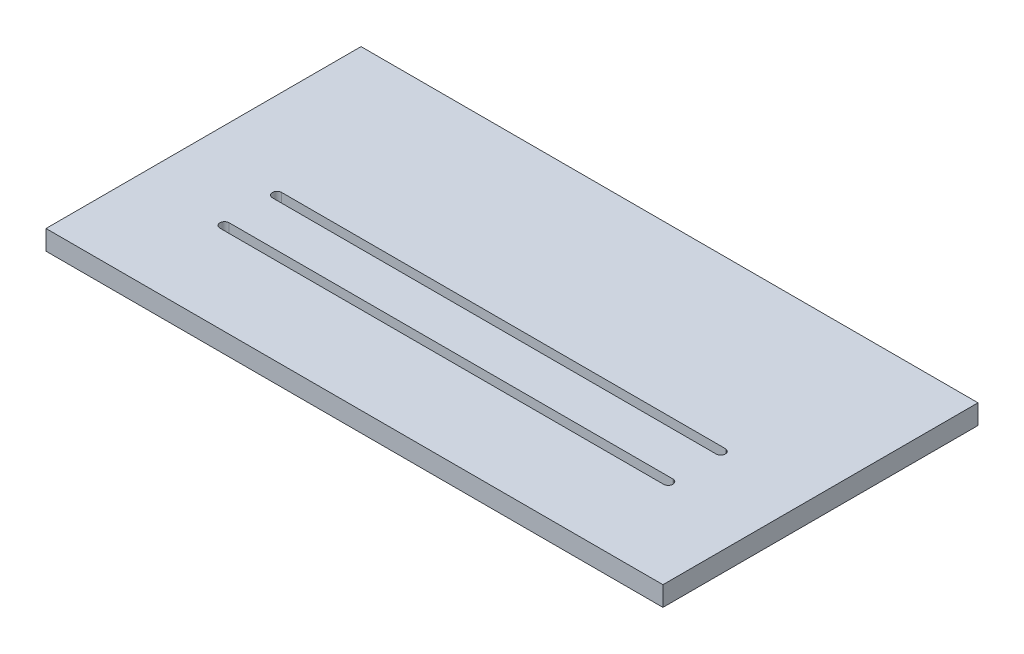
SolidWorks part; units mm, degrees
material "Acrylic (Medium-high impact)"
ref_plane "Front Plane" through (0, 0, 0) normal (0, 0, 1) x (1, 0, 0)
ref_plane "Top Plane" through (0, 0, 0) normal (0, 1, 0) x (1, 0, 0)
ref_plane "Right Plane" through (0, 0, 0) normal (1, 0, 0) x (0, 0, -1)
sketch "Sketch1" plane through (0, 0, 0) normal (0, 1, 0) x (1, 0, 0)
  line L1 (-149.225, -76.2) -> (149.225, -76.2)
  line L2 (-149.225, -76.2) -> (-149.225, 76.2)
  line L3 (-149.225, 76.2) -> (149.225, 76.2)
  line L4 (149.225, -76.2) -> (149.225, 76.2)
  line L5 (-149.225, -76.2) -> (149.225, 76.2) construction
  line L6 (-149.225, 76.2) -> (149.225, -76.2) construction
  line L7 (73.025, -76.2) -> (-130.175, -76.2)
  line L11 (-384.175, -76.2) -> (-231.775, -76.2)
  point P0 (0, 0)
  dimension "D1" = 298.45
  dimension "D2" = 152.4
extrude "Boss-Extrude1" add sketch "Sketch1" along normal mid plane 9.525 contours L1 L4 L3 L2
sketch "Sketch2" [suppressed] plane through (0, 0, 0) normal (0, 1, 0) x (1, 0, 0)
  line L0 (-250.825, -28.575) -> (250.825, -28.575) construction
  line L1 (161.925, -28.575) -> (60.325, -28.575)
  line L2 (161.925, -28.575) -> (161.925, -92.075)
  line L3 (161.925, -92.075) -> (60.325, -92.075)
  line L4 (60.325, -28.575) -> (60.325, -92.075)
  line L5 (0, -5.2388) -> (0, 5.2388) construction
  line L6 (-79.375, -28.575) -> (-168.275, -28.575)
  line L7 (-79.375, -28.575) -> (-79.375, -92.075)
  line L8 (-79.375, -92.075) -> (-168.275, -92.075)
  line L9 (-168.275, -28.575) -> (-168.275, -92.075)
  line L10 (250.825, -28.575) -> (250.825, 28.575) construction
  line L11 (-250.825, -28.575) -> (-250.825, 28.575) construction
  line L12 (-250.825, 28.575) -> (250.825, 28.575) construction
  line L13 (250.825, -28.575) -> (250.825, 28.575) construction
  line L14 (161.925, -28.575) -> (250.825, -28.575)
  line L15 (161.925, -28.575) -> (161.925, -71.755)
  line L16 (161.925, -71.755) -> (250.825, -71.755)
  line L17 (250.825, -28.575) -> (250.825, -71.755)
  line L18 (-250.825, -28.575) -> (-250.825, 28.575) construction
  line L19 (-79.375, -28.575) -> (60.325, -28.575)
  line L20 (-79.375, -28.575) -> (-79.375, -53.975)
  line L21 (-79.375, -53.975) -> (60.325, -53.975)
  line L22 (60.325, -28.575) -> (60.325, -53.975)
  line L23 (-168.275, -28.575) -> (-250.825, -28.575)
  line L24 (-168.275, -28.575) -> (-168.275, -71.755)
  line L25 (-168.275, -71.755) -> (-250.825, -71.755)
  line L26 (-250.825, -28.575) -> (-250.825, -71.755)
  point P19 (60.325, -92.075)
  dimension "D1" = 139.7
  dimension "D2" = 88.9
  dimension "D3" = 82.55
  dimension "D4" = 79.375
  dimension "D5" = 120.65
  dimension "D6" = 43.18
  dimension "D7" = 25.4
  dimension "D8" = 43.18
extrude "Boss-Extrude2" [suppressed] add sketch "Sketch2" along normal mid plane 9.525 contours L6 L9 L8 L7 | L23 L26 L25 L9 | L7 L21 L4 L19 | L17 L14 L2 L16
sketch "Sketch3" [suppressed] plane through (0, 4.7625, 0) normal (0, 1, 0) x (1, 0, 0)
  line L0 (-149.225, 247.65) -> (149.225, 247.65) construction
  line L1 (-98.425, 12.7) -> (98.425, 12.7)
  line L2 (-98.425, 12.7) -> (-98.425, -101.6)
  line L3 (-98.425, -101.6) -> (98.425, -101.6)
  line L4 (98.425, 12.7) -> (98.425, -101.6)
  line L5 (-98.425, 12.7) -> (98.425, -101.6) construction
  line L6 (-98.425, -101.6) -> (98.425, 12.7) construction
  line L7 (-149.225, -247.65) -> (149.225, -247.65) construction
  point P0 (0, -44.45)
  point P7 (0, 247.65)
  point P8 (0, 12.7)
  dimension "D1" = 196.85
  dimension "D2" = 114.3
  dimension "D3" = 203.2
extrude "Cut-Extrude1" [suppressed] cut sketch "Sketch3" against normal through all and the other way through all
sketch "Sketch4" plane through (0, -4.7625, 0) normal (0, -1, 0) x (1, 0, 0)
  line L0 (-107.315, 31.75) -> (107.315, 31.75) construction
  line L1 (-107.315, 33.9979) -> (107.315, 33.9979)
  line L2 (-107.315, 29.5021) -> (107.315, 29.5021)
  line L3 (-107.315, 6.35) -> (107.315, 6.35) construction
  line L4 (-107.315, 8.5979) -> (107.315, 8.5979)
  line L5 (-107.315, 4.1021) -> (107.315, 4.1021)
  arc A0 (-107.315, 33.9979) -> (-107.315, 29.5021) centre (-107.315, 31.75) ccw
  arc A1 (107.315, 29.5021) -> (107.315, 33.9979) centre (107.315, 31.75) ccw
  arc A2 (-107.315, 8.5979) -> (-107.315, 4.1021) centre (-107.315, 6.35) ccw
  arc A3 (107.315, 4.1021) -> (107.315, 8.5979) centre (107.315, 6.35) ccw
  point P0 (-107.315, 31.75)
  point P1 (107.315, 31.75)
  point P3 (107.315, 6.35)
  point P5 (-107.315, 6.35)
  point P10 (0, 31.75)
  point P15 (0, 6.35)
  dimension "D1" = 4.4958
  dimension "D2" = 4.4958
extrude "Cut-Extrude2" cut sketch "Sketch4" against normal through all
sketch "Sketch5" [suppressed] plane through (0, -4.7625, 0) normal (0, -1, 0) x (1, 0, 0)
  line L0 (69.85, 79.375) -> (69.85, -9.525) construction
  line L1 (60.325, 53.975) -> (60.325, 92.075) construction
  line L2 (161.925, 92.075) -> (60.325, 92.075) construction
  line L3 (-247.65, -22.225) -> (247.65, -22.225) construction
  line L4 (69.85, 79.375) -> (69.85, -9.525) construction
  line L5 (72.0979, 79.375) -> (72.0979, -9.525)
  line L6 (67.6021, 79.375) -> (67.6021, -9.525)
  line L7 (-88.9, 79.375) -> (-88.9, -9.525) construction
  line L8 (-79.375, 53.975) -> (-79.375, 92.075) construction
  line L9 (-79.375, 92.075) -> (-168.275, 92.075) construction
  line L10 (-88.9, 79.375) -> (-88.9, -9.525) construction
  line L11 (-86.6521, 79.375) -> (-86.6521, -9.525)
  line L12 (-91.1479, 79.375) -> (-91.1479, -9.525)
  arc A0 (72.0979, 79.375) -> (67.6021, 79.375) centre (69.85, 79.375) ccw
  arc A1 (67.6021, -9.525) -> (72.0979, -9.525) centre (69.85, -9.525) ccw
  arc A2 (-86.6521, 79.375) -> (-91.1479, 79.375) centre (-88.9, 79.375) ccw
  arc A3 (-91.1479, -9.525) -> (-86.6521, -9.525) centre (-88.9, -9.525) ccw
  point P8 (69.85, 34.925)
  point P19 (-88.9, 34.925)
  dimension "D1" = 9.525
  dimension "D2" = 12.7
  dimension "D3" = 12.7
  dimension "D4" = 4.4958
  dimension "D5" = 9.525
  dimension "D6" = 12.7
  dimension "D7" = 12.7
  dimension "D8" = 4.4958
extrude "Cut-Extrude3" [suppressed] cut sketch "Sketch5" against normal through all contours L12 A3 L11 A2 | L6 A1 L5 A0
sketch "Sketch6" [suppressed] plane through (0, 3.175, 0) normal (0, 1, 0) x (1, 0, 0)
  line L0 (-79.375, -38.1) -> (-79.375, 38.1) construction
  line L1 (-88.9, -50.8) -> (-88.9, 50.8) construction
  line L2 (-88.9, -50.8) -> (88.9, -50.8) construction
  line L3 (-88.9, 50.8) -> (88.9, 50.8) construction
  line L4 (79.375, -38.1) -> (79.375, 38.1) construction
  line L5 (88.9, -50.8) -> (88.9, 50.8) construction
  line L6 (-79.375, -38.1) -> (-79.375, 38.1) construction
  line L7 (-81.6229, -38.1) -> (-81.6229, 38.1)
  line L8 (-77.1271, -38.1) -> (-77.1271, 38.1)
  line L9 (79.375, -38.1) -> (79.375, 38.1) construction
  line L10 (77.1271, -38.1) -> (77.1271, 38.1)
  line L11 (81.6229, -38.1) -> (81.6229, 38.1)
  arc A0 (-81.6229, -38.1) -> (-77.1271, -38.1) centre (-79.375, -38.1) ccw
  arc A1 (-77.1271, 38.1) -> (-81.6229, 38.1) centre (-79.375, 38.1) ccw
  arc A2 (77.1271, -38.1) -> (81.6229, -38.1) centre (79.375, -38.1) ccw
  arc A3 (81.6229, 38.1) -> (77.1271, 38.1) centre (79.375, 38.1) ccw
  point P12 (-79.375, 0)
  point P17 (79.375, 0)
  dimension "D1" = 9.525
  dimension "D2" = 12.7
  dimension "D3" = 12.7
  dimension "D4" = 9.525
  dimension "D5" = 12.7
  dimension "D6" = 12.7
  dimension "D7" = 4.4958
  dimension "D8" = 4.4958
extrude "Cut-Extrude4" [suppressed] cut sketch "Sketch6" against normal through all
sketch "Sketch7" [suppressed] plane through (0, 4.7625, 0) normal (0, 1, 0) x (1, 0, 0)
  point P0 (115.1313, 66.802)
  point P1 (139.827, 42.1063)
  point P3 (-139.827, 42.1063)
  point P5 (-115.1313, 66.802)
hole_wizard "#12 Clearance Hole1" [suppressed] positions "Sketch8" profile "Sketch9" hole size "#12" standard "ANSI Inch"
sketch "Sketch8" [suppressed] plane through (0, 4.7625, 0) normal (0, 1, 0) x (1, 0, 0)
  point P0 (-139.827, 42.1063)
  point P3 (-115.1313, 66.802)
  point P6 (115.1313, 66.802)
  point P9 (139.827, 42.1063)
sketch "Sketch9" plane through (-139.827, 4.7625, -42.1063) normal (1, 0, 0) x (0, 0, 1)
  line L0 (0, 0) -> (0, 18.1964)
  line L1 (0, 18.1964) -> (2.8067, 16.51)
  line L2 (2.8067, 16.51) -> (2.8067, 0)
  line L5 (2.8067, 0) -> (0, 0)
  line L10 (0, 18.1964) -> (-2.8067, 16.51) construction
  line L11 (0, -6.35) -> (0, 107.95) construction
  dimension "Hole Dia." = 5.6134
  dimension "Hole Depth" = 16.51
  dimension "Drill Angle" = 118
sketch "Sketch10" [suppressed] plane through (0, -4.7625, 0) normal (0, -1, 0) x (1, 0, 0)
  point P0 (223.8375, -6.35)
  point P1 (223.8375, 19.05)
  point P3 (-223.8375, 19.05)
  point P5 (-223.8375, -6.35)
hole_wizard "#12 Clearance Hole3" [suppressed] positions "Sketch11" profile "Sketch12" hole size "#12" standard "ANSI Inch"
sketch "Sketch11" plane through (0, -4.7625, 0) normal (0, -1, 0) x (-1, 0, 0)
  point P0 (-223.8375, -19.05)
  point P3 (-223.8375, 6.35)
  point P6 (223.8375, -19.05)
  point P9 (223.8375, 6.35)
sketch "Sketch12" plane through (223.8375, -4.7625, 19.05) normal (1, 0, 0) x (0, 0, -1)
  line L0 (0, 0) -> (0, 18.1964)
  line L1 (0, 18.1964) -> (2.8067, 16.51)
  line L2 (2.8067, 16.51) -> (2.8067, 0)
  line L5 (2.8067, 0) -> (0, 0)
  line L10 (0, 18.1964) -> (-2.8067, 16.51) construction
  line L11 (0, -6.35) -> (0, 107.95) construction
  dimension "Hole Dia." = 5.6134
  dimension "Hole Depth" = 16.51
  dimension "Drill Angle" = 118
sketch "Sketch13" [suppressed] plane through (0, -4.7625, 0) normal (0, -1, 0) x (1, 0, 0)
  point P0 (133.35, -223.8375)
  point P1 (107.95, -223.8375)
  point P3 (-107.95, -223.8375)
  point P5 (-133.35, -223.8375)
  point P7 (133.35, 223.8375)
  point P9 (107.95, 223.8375)
  point P11 (-107.95, 223.8375)
  point P13 (-133.35, 223.8375)
hole_wizard "#12 Clearance Hole2" [suppressed] positions "Sketch14" profile "Sketch15" hole size "#12" standard "ANSI Inch"
sketch "Sketch14" plane through (0, -4.7625, 0) normal (0, -1, 0) x (-1, 0, 0)
  point P0 (107.95, -223.8375)
  point P3 (133.35, -223.8375)
  point P6 (133.35, 223.8375)
  point P9 (107.95, 223.8375)
  point P12 (-133.35, 223.8375)
  point P15 (-107.95, 223.8375)
  point P18 (-133.35, -223.8375)
  point P21 (-107.95, -223.8375)
sketch "Sketch15" plane through (-107.95, -4.7625, 223.8375) normal (1, 0, 0) x (0, 0, -1)
  line L0 (0, 0) -> (0, 18.1964)
  line L1 (0, 18.1964) -> (2.8067, 16.51)
  line L2 (2.8067, 16.51) -> (2.8067, 0)
  line L5 (2.8067, 0) -> (0, 0)
  line L10 (0, 18.1964) -> (-2.8067, 16.51) construction
  line L11 (0, -6.35) -> (0, 107.95) construction
  dimension "Hole Dia." = 5.6134
  dimension "Hole Depth" = 16.51
  dimension "Drill Angle" = 118
sketch "Sketch16" [suppressed] plane through (0, 3.175, 0) normal (0, 1, 0) x (1, 0, 0)
  line L0 (88.9, -50.8) -> (88.9, 50.8) construction
  line L1 (-88.9, -50.8) -> (-88.9, 50.8) construction
  line L2 (-88.9, -50.8) -> (88.9, -50.8) construction
  point P0 (79.375, -38.1)
  point P1 (-79.375, -38.1)
  dimension "D1" = 9.525
  dimension "D2" = 9.525
  dimension "D3" = 12.7
hole_wizard "#8 Clearance Hole1" [suppressed] positions "Sketch17" profile "Sketch19" hole size "#8" standard "ANSI Inch"
sketch "Sketch17" plane through (0, 3.175, 0) normal (0, 1, 0) x (1, 0, 0)
  point P0 (79.375, -38.1)
  point P3 (-79.375, -38.1)
sketch "Sketch19" plane through (79.375, 3.175, 38.1) normal (1, 0, 0) x (0, 0, 1)
  line L0 (0, 0) -> (0, 12.0187)
  line L1 (0, 12.0187) -> (2.2479, 10.668)
  line L2 (2.2479, 10.668) -> (2.2479, 0)
  line L5 (2.2479, 0) -> (0, 0)
  line L10 (0, 12.0187) -> (-2.2479, 10.668) construction
  line L11 (0, -6.35) -> (0, 107.95) construction
  dimension "Hole Dia." = 4.4958
  dimension "Hole Depth" = 10.668
  dimension "Drill Angle" = 118
sketch "Sketch20" [suppressed] plane through (0, -4.7625, 0) normal (0, -1, 0) x (1, 0, 0)
  line L0 (-149.225, 247.65) -> (149.225, 247.65) construction
  line L1 (23.9395, 147.5105) -> (-23.9395, 147.5105)
  line L2 (23.9395, 147.5105) -> (23.9395, 195.3895)
  line L3 (23.9395, 195.3895) -> (-23.9395, 195.3895)
  line L4 (-23.9395, 147.5105) -> (-23.9395, 195.3895)
  line L5 (23.9395, 147.5105) -> (-23.9395, 195.3895) construction
  line L6 (23.9395, 195.3895) -> (-23.9395, 147.5105) construction
  line L8 (38.1, 155.575) -> (-38.1, 155.575) construction
  line L9 (38.1, 155.575) -> (38.1, 187.325) construction
  line L10 (38.1, 187.325) -> (-38.1, 187.325) construction
  line L11 (-38.1, 155.575) -> (-38.1, 187.325) construction
  point P0 (0, 171.45)
  point P7 (0, 247.65)
  point P8 (38.1, 155.575)
  point P9 (38.1, 187.325)
  point P10 (-38.1, 155.575)
  point P11 (-38.1, 187.325)
  point P18 (0, 187.325)
  point P19 (0, 195.3895)
  point P20 (-38.1, 171.45)
  point P21 (-23.9395, 171.45)
  dimension "D1" = 47.879
  dimension "D2" = 47.879
  dimension "D3" = 38.1
  dimension "D4" = 15.875
  dimension "D5" = 76.2
extrude "Cut-Extrude5" [suppressed] cut sketch "Sketch20" against normal through all contours L1 L4 L3 L2
hole_wizard "#10 Clearance Hole1" [suppressed] positions "Sketch21" profile "Sketch22" hole size "#10" standard "ANSI Inch"
sketch "Sketch21" plane through (0, -4.7625, 0) normal (0, -1, 0) x (-1, 0, 0)
  point P0 (-38.1, -155.575)
  point P3 (38.1, -155.575)
  point P6 (38.1, -187.325)
  point P9 (-38.1, -187.325)
sketch "Sketch22" plane through (38.1, -4.7625, 155.575) normal (1, 0, 0) x (0, 0, -1)
  line L0 (0, 0) -> (0, 12.2018)
  line L1 (0, 12.2018) -> (2.5527, 10.668)
  line L2 (2.5527, 10.668) -> (2.5527, 0)
  line L5 (2.5527, 0) -> (0, 0)
  line L10 (0, 12.2018) -> (-2.5527, 10.668) construction
  line L11 (0, -6.35) -> (0, 107.95) construction
  dimension "Hole Dia." = 5.1054
  dimension "Hole Depth" = 10.668
  dimension "Drill Angle" = 118
sketch "Sketch23" [suppressed] plane through (-250.825, 0, 0) normal (-1, 0, 0) x (0, 0, 1)
  line L4 (-28.575, -4.7625) -> (71.755, -4.7625)
  line L5 (71.755, -4.7625) -> (71.755, 4.7625)
  line L6 (71.755, 4.7625) -> (-28.575, 4.7625)
  line L7 (-28.575, 4.7625) -> (-28.575, -4.7625)
  line L8 (-28.575, -4.7625) -> (71.755, -4.7625)
  line L9 (71.755, -4.7625) -> (71.755, 4.7625)
  line L10 (71.755, 4.7625) -> (-28.575, 4.7625)
  line L11 (-28.575, 4.7625) -> (-28.575, -4.7625)
  dimension "D1" = 0
extrude "Boss-Extrude3" [suppressed] add sketch "Sketch23" along normal blind 6.35
mirror "Mirror1" [suppressed] about plane through (0, 0, 0) normal (1, 0, 0)
